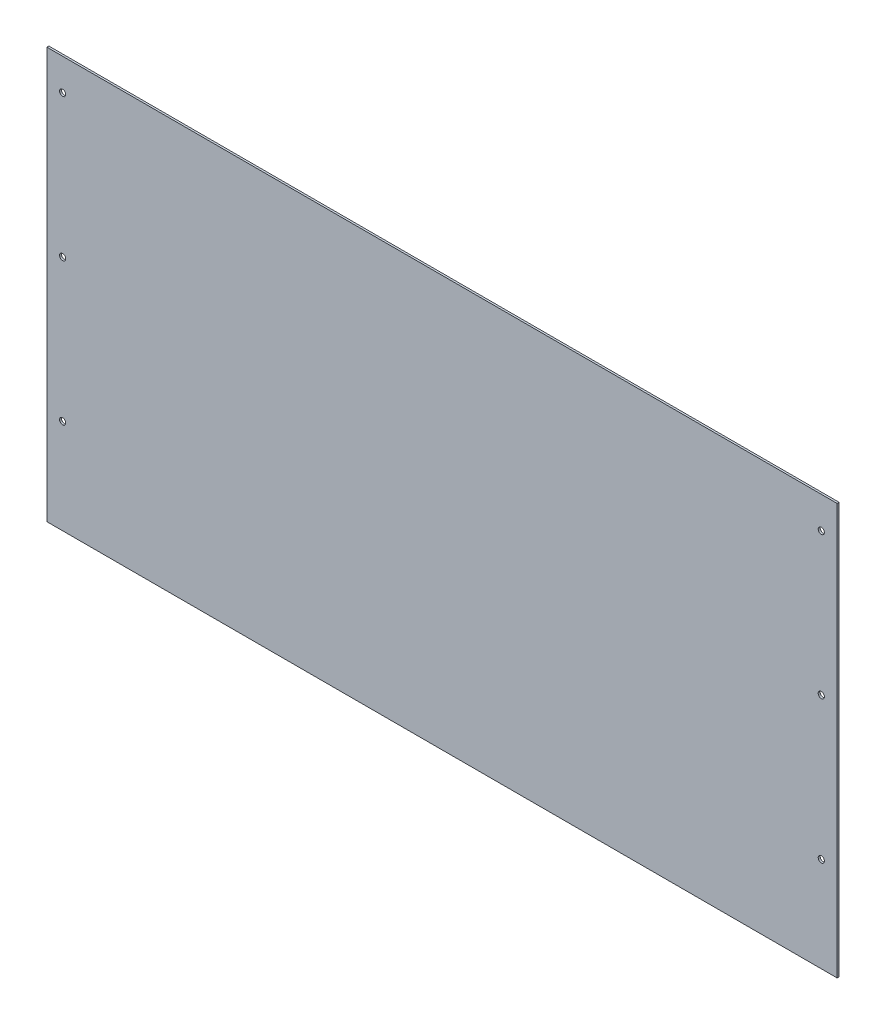
SolidWorks part; units mm, degrees
material "ABS PC"
ref_plane "Front Plane" through (0, 0, 0) normal (0, 0, 1) x (1, 0, 0)
ref_plane "Top Plane" through (0, 0, 0) normal (0, 1, 0) x (1, 0, 0)
ref_plane "Right Plane" through (0, 0, 0) normal (1, 0, 0) x (0, 0, -1)
sketch "Sketch1" plane through (0, 0, 0) normal (0, 0, 1) x (1, 0, 0)
  line L1 (-317.5, -165.1) -> (317.5, -165.1)
  line L2 (-317.5, -165.1) -> (-317.5, 165.1)
  line L3 (-317.5, 165.1) -> (317.5, 165.1)
  line L4 (317.5, -165.1) -> (317.5, 165.1)
  line L5 (0, 165.1) -> (0, -165.1) construction
  line L6 (-317.5, 0) -> (317.5, 0) construction
  point P0 (0, 0)
  point P4 (-222.25, 0)
  point P5 (222.25, 0)
  point P6 (0, 115.57)
  point P7 (0, -115.57)
  dimension "Length" = 635
  dimension "Width" = 330.2
  dimension "Break" = 95.25
  dimension "D2" = 95.25
  dimension "D1" = 49.53
  dimension "D3" = 49.53
sketch "Sketch2" plane through (0, 0, 0) normal (1, 0, 0) x (0, 0, -1)
  line L0 (-0.7937, -165.1) -> (0.7937, -165.1)
  dimension "Thickness" = 1.5875
sketch "Sketch3" plane through (0, 0, 0) normal (0, 0, 1) x (1, 0, 0)
  line L0 (-317.5, -165.1) -> (-317.5, 165.1) construction
  line L1 (-317.5, -165.1) -> (317.5, -165.1) construction
  line L2 (317.5, -165.1) -> (317.5, 165.1) construction
  line L3 (-317.5, 165.1) -> (317.5, 165.1) construction
  line L4 (-317.5, -165.1) -> (-317.5, 165.1)
  line L5 (-317.5, -165.1) -> (317.5, -165.1)
  line L6 (317.5, -165.1) -> (317.5, 165.1)
  line L7 (-317.5, 165.1) -> (317.5, 165.1)
extrude "Boss-Extrude1" add sketch "Sketch3" along normal mid plane 1.5875
sketch "Sketch4" plane through (0, 0, 0.7937) normal (0, 0, 1) x (1, 0, 0)
  line L0 (-317.5, 165.1) -> (-304.8, 165.1) construction
  line L1 (317.5, 165.1) -> (-317.5, 165.1) construction
  line L2 (-304.8, 165.1) -> (-304.8, 139.7) construction
  line L3 (-304.8, 139.7) -> (-304.8, 25.4) construction
  line L4 (-304.8, 25.4) -> (-304.8, -88.9) construction
  line L5 (317.5, 165.1) -> (304.8, 165.1) construction
  line L6 (304.8, 165.1) -> (304.8, 139.7) construction
  line L7 (304.8, 139.7) -> (304.8, 25.4) construction
  line L8 (304.8, 25.4) -> (304.8, -88.9) construction
  dimension "D1" = 25.4
  dimension "D2" = 114.3
  dimension "D3" = 114.3
hole_wizard "#10 Clearance Hole1" positions "Sketch5" profile "Sketch6" hole size "#10" standard "ANSI Inch" end condition through all
sketch "Sketch5" plane through (0, 0, 0.7937) normal (0, 0, 1) x (1, 0, 0)
  point P0 (-304.8, 139.7)
  point P4 (-304.8, 25.4)
  point P7 (-304.8, -88.9)
  point P10 (304.7359, 139.7)
  point P12 (304.7359, 25.4)
  point P14 (304.7359, -88.9)
sketch "Sketch6" plane through (-304.8, 139.7, 0.7937) normal (1, 0, 0) x (0, -1, 0)
  line L0 (0, 0) -> (0, 1.5875)
  line L1 (0, 1.5875) -> (2.4892, 1.5875)
  line L2 (2.4892, 1.5875) -> (2.4892, 0)
  line L5 (2.4892, 0) -> (0, 0)
  line L11 (0, -6.35) -> (0, 107.95) construction
  dimension "Thru Hole Dia." = 4.9784
  dimension "Thru Hole Depth" = 1.5875
equation "\"D1@Boss-Extrude1\"=\"thickness@sketch2\""
equation "\"Break@Sketch1\" = \"Length@Sketch1\" * 0.15"
equation "\"D2@Sketch1\" = \"Break@Sketch1\""
equation "\"D1@Sketch1\"=\"Width@Sketch1\"*0.15"
equation "\"D3@Sketch1\"=\"D1@Sketch1\""
